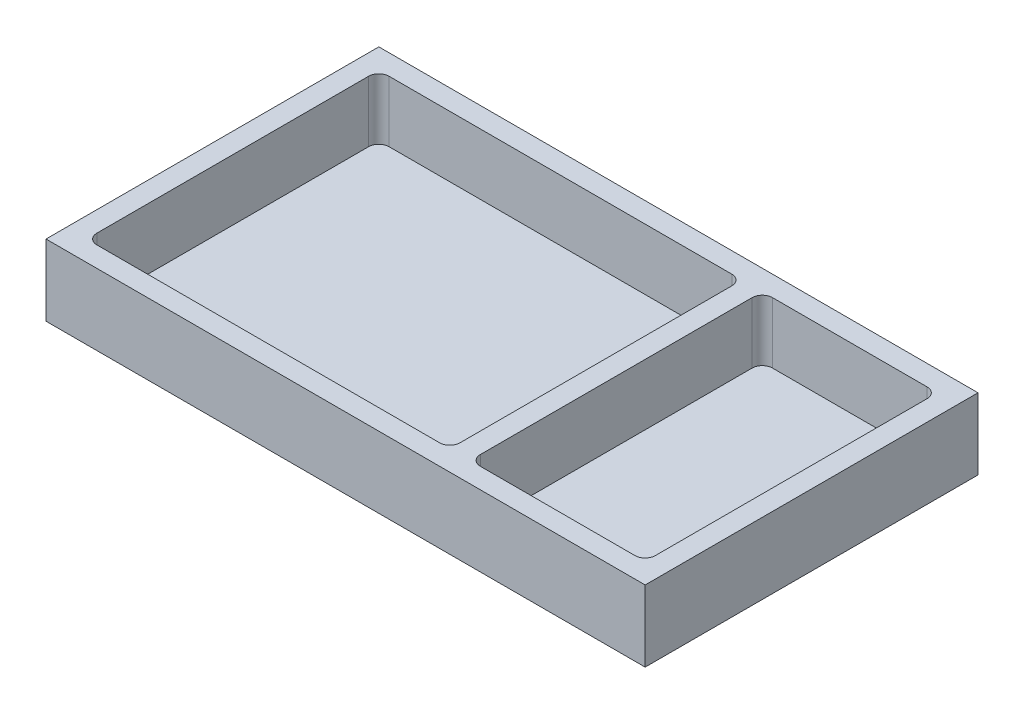
SolidWorks part; units mm, degrees
ref_plane "Front Plane" through (0, 0, 0) normal (0, 0, 1) x (1, 0, 0)
ref_plane "Top Plane" through (0, 0, 0) normal (0, 1, 0) x (1, 0, 0)
ref_plane "Right Plane" through (0, 0, 0) normal (1, 0, 0) x (0, 0, -1)
sketch "Sketch11" plane through (0, 0, 0) normal (0, 1, 0) x (1, 0, 0)
  line L0 (9.525, 6.35) -> (116.5413, 6.35)
  line L1 (0, 0) -> (187.0518, 0)
  line L2 (0, 0) -> (0, 103.9105)
  line L3 (0, 103.9105) -> (187.0518, 103.9105)
  line L4 (187.0518, 0) -> (187.0518, 103.9105)
  line L5 (180.7018, 9.525) -> (180.7018, 94.3855)
  line L6 (9.525, 97.5605) -> (116.5413, 97.5605)
  line L7 (6.35, 9.525) -> (6.35, 94.3855)
  line L8 (119.7163, 94.3855) -> (119.7163, 9.525)
  line L9 (126.0663, 94.3855) -> (126.0663, 9.525)
  line L10 (129.2413, 97.5605) -> (177.5268, 97.5605)
  line L11 (129.2413, 6.35) -> (177.5268, 6.35)
  line L12 (6.35, 97.5605) -> (180.7018, 97.5605) construction
  line L13 (119.7163, 97.5605) -> (119.7163, 6.35) construction
  line L14 (6.35, 6.35) -> (180.7018, 6.35) construction
  line L15 (126.0663, 97.5605) -> (126.0663, 6.35) construction
  line L16 (180.7018, 6.35) -> (180.7018, 97.5605) construction
  line L17 (6.35, 6.35) -> (6.35, 97.5605) construction
  arc A0 (119.7163, 94.3855) -> (116.5413, 97.5605) centre (116.5413, 94.3855) ccw
  arc A1 (129.2413, 97.5605) -> (126.0663, 94.3855) centre (129.2413, 94.3855) ccw
  arc A2 (180.7018, 94.3855) -> (177.5268, 97.5605) centre (177.5268, 94.3855) ccw
  arc A3 (180.7018, 9.525) -> (177.5268, 6.35) centre (177.5268, 9.525) cw
  arc A4 (126.0663, 9.525) -> (129.2413, 6.35) centre (129.2413, 9.525) ccw
  arc A5 (119.7163, 9.525) -> (116.5413, 6.35) centre (116.5413, 9.525) cw
  arc A6 (6.35, 94.3855) -> (9.525, 97.5605) centre (9.525, 94.3855) cw
  arc A7 (9.525, 6.35) -> (6.35, 9.525) centre (9.525, 9.525) cw
  dimension "D3" = 3.175
  dimension "D1" = 6.35
  dimension "D2" = 6.35
extrude "Extrude3" add sketch "Sketch11" along normal blind 19.05
sketch "Sketch12" plane through (0, 0, 0) normal (0, 1, 0) x (1, 0, 0)
  line L1 (0, 103.9105) -> (187.0518, 103.9105)
  line L2 (0, 103.9105) -> (0, 0)
  line L3 (0, 0) -> (187.0518, 0)
  line L4 (187.0518, 103.9105) -> (187.0518, 0)
extrude "Extrude4" add sketch "Sketch12" against normal blind 3.175
ref_plane "Plane5" through (-12.7, 0, 0) normal (-1, 0, 0) x (0, 0, 1)
sketch "Sketch13" plane through (-12.7, 0, 0) normal (-1, 0, 0) x (0, 0, 1)
  circle A0 centre (-51.9553, 9.2188) radius 5.973
